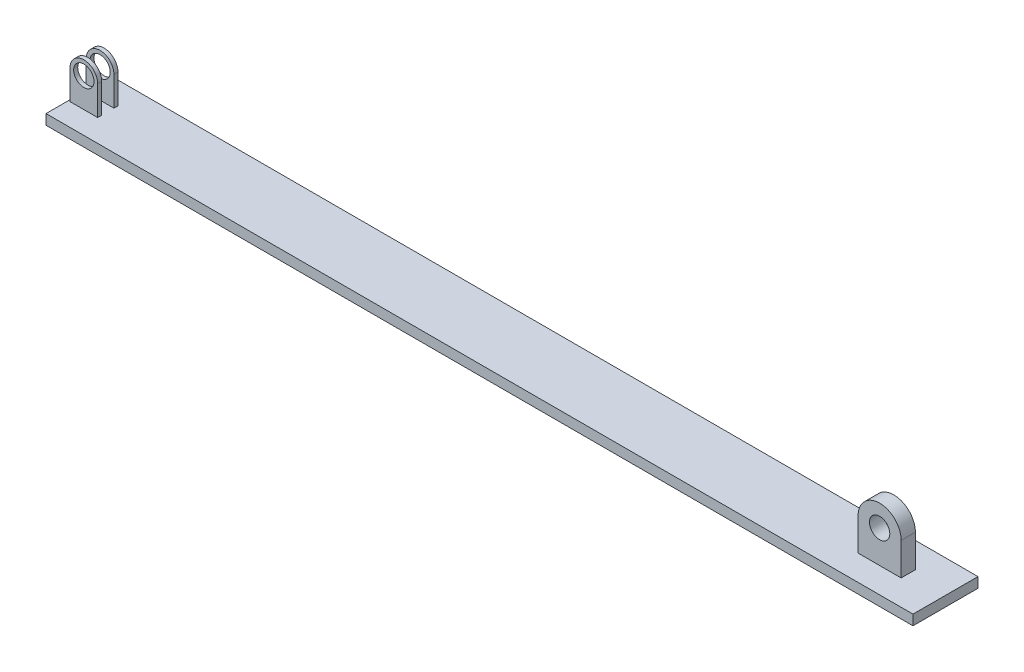
SolidWorks part; units mm, degrees
material "6061 Alloy"
ref_plane "Front Plane" through (0, 0, 0) normal (0, 0, 1) x (1, 0, 0)
ref_plane "Top Plane" through (0, 0, 0) normal (0, 1, 0) x (1, 0, 0)
ref_plane "Right Plane" through (0, 0, 0) normal (1, 0, 0) x (0, 0, -1)
sketch "Sketch1" plane through (0, 0, 0) normal (0, 0, -1) x (1, 0, 0)
  line L0 (0, -17.3848) -> (0, 17.3848) construction
  line L1 (0, 2.5) -> (426.72, 2.5)
  line L2 (0, 2.5) -> (0, -2.5)
  line L3 (0, -2.5) -> (426.72, -2.5)
  line L4 (426.72, 2.5) -> (426.72, -2.5)
  line L5 (426.72, 0) -> (0, 0) construction
  dimension "D1" = 5
  dimension "D2" = 426.72
extrude "Extrude2" add sketch "Sketch1" along normal mid plane 32
sketch "Sketch2" plane through (0, 0, 0) normal (0, 0, 1) x (1, 0, 0)
  line L0 (7.6165, 2.5) -> (7.6165, 11.837) construction
  line L1 (0, 2.5) -> (426.72, 2.5) construction
  line L2 (0.8031, 2.5) -> (0.8031, 16.9215)
  line L3 (14.4299, 2.5) -> (14.4299, 16.9215)
  line L4 (0.8031, 2.5) -> (14.4299, 2.5)
  arc A0 (0.8031, 16.9215) -> (14.4299, 16.9215) centre (7.6165, 16.9215) cw
  circle A1 centre (7.6165, 16.9215) radius 5
  dimension "D1" = 10
extrude "Extrude3" add sketch "Sketch2" along normal mid plane 10
sketch "Sketch3" plane through (0.8031, 0, 0) normal (-1, 0, 0) x (0, 0, 1)
  line L0 (-16, 2.5) -> (16, 2.5) construction
  line L1 (-3, 2.5) -> (3, 2.5)
  line L2 (-3, 2.5) -> (-3, 43.4954)
  line L3 (-3, 43.4954) -> (3, 43.4954)
  line L4 (3, 2.5) -> (3, 43.4954)
  line L5 (0, 43.4954) -> (0, 2.5) construction
  line L6 (0, -17.3848) -> (0, 17.3848) construction
  dimension "D1" = 6
extrude "Cut-Extrude1" cut sketch "Sketch3" against normal up to surface (13.6268 mm away) up to face at (14.4299, 9.7108, 0)
sketch "Sketch4" plane through (0, 0, 0) normal (0, 0, 1) x (1, 0, 0)
  line L0 (397.8057, 2.5) -> (397.8057, 18.5157) construction
  line L1 (0, 2.5) -> (426.72, 2.5) construction
  line L2 (408.3986, 2.5) -> (408.3986, 18.5157)
  line L3 (387.2127, 2.5) -> (387.2127, 18.5157)
  line L4 (387.2127, 2.5) -> (408.3986, 2.5)
  arc A0 (408.3986, 18.5157) -> (387.2127, 18.5157) centre (397.8057, 18.5157) ccw
  circle A1 centre (397.8057, 18.5157) radius 5
  dimension "D1" = 10
extrude "Extrude4" add sketch "Sketch4" along normal mid plane 7
